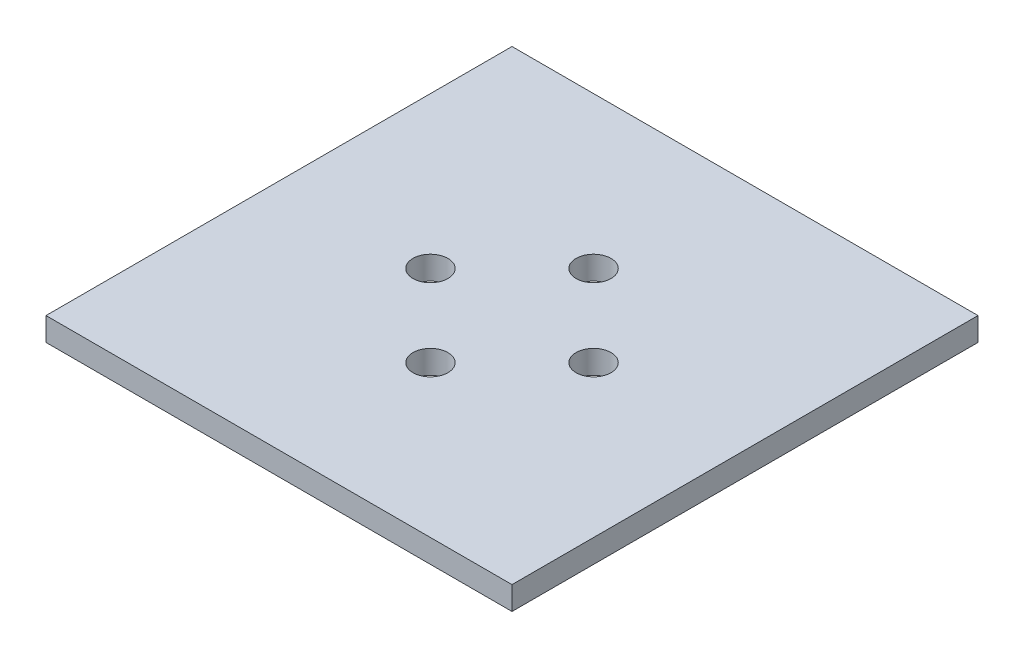
SolidWorks part; units mm, degrees
ref_plane "Спереди" through (0, 0, 0) normal (0, 0, 1) x (1, 0, 0)
ref_plane "Сверху" through (0, 0, 0) normal (0, 1, 0) x (1, 0, 0)
ref_plane "Справа" through (0, 0, 0) normal (1, 0, 0) x (0, 0, -1)
sketch "Эскиз1" plane through (0, 0, 0) normal (0, 1, 0) x (1, 0, 0)
  line L1 (0, 0) -> (40, 0)
  line L2 (0, 0) -> (0, 40)
  line L3 (0, 40) -> (40, 40)
  line L4 (40, 0) -> (40, 40)
  circle A0 centre (20, 20) radius 7 construction
  circle A1 centre (13, 20) radius 1.5
  circle A2 centre (20, 27) radius 1.5
  circle A3 centre (27, 20) radius 1.5
  circle A4 centre (20, 13) radius 1.5
  dimension "D1" = 14
  dimension "D2" = 3
  dimension "D3" = 20
  dimension "D4" = 20
  dimension "D5" = 40
  dimension "D6" = 40
extrude "Бобышка-Вытянуть1" add sketch "Эскиз1" along normal blind 2
